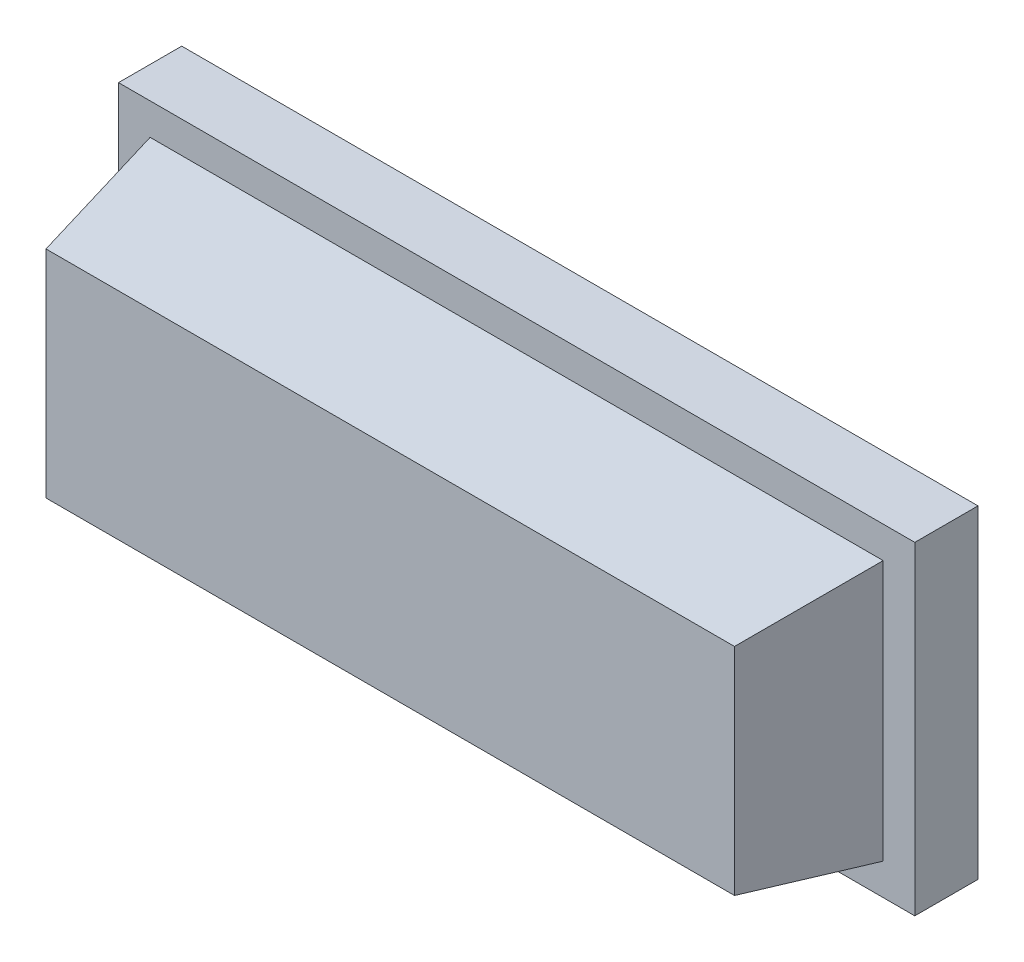
SolidWorks part; units mm, degrees
ref_plane "Front Plane" through (0, 0, 0) normal (0, 0, 1) x (1, 0, 0)
ref_plane "Top Plane" through (0, 0, 0) normal (0, 1, 0) x (1, 0, 0)
ref_plane "Right Plane" through (0, 0, 0) normal (1, 0, 0) x (0, 0, -1)
sketch "Sketch1" plane through (0, 0, 0) normal (0, 0, 1) x (1, 0, 0)
  line L0 (-1.6, -0.65) -> (1.6, 0.65) construction
  line L1 (-1.6, 0.65) -> (1.6, 0.65)
  line L2 (-1.6, 0.65) -> (-1.6, -0.65)
  line L3 (-1.6, -0.65) -> (1.6, -0.65)
  line L4 (1.6, 0.65) -> (1.6, -0.65)
  point P4 (0, 0)
  dimension "D1" = 3.2
  dimension "D2" = 1.3
extrude "Boss-Extrude1" add sketch "Sketch1" along normal blind 0.254
sketch "Sketch2" plane through (0, 0, 0.254) normal (0, 0, 1) x (1, 0, 0)
  line L0 (-1.473, -0.523) -> (1.473, 0.523) construction
  line L1 (-1.473, 0.523) -> (1.473, 0.523)
  line L2 (-1.473, 0.523) -> (-1.473, -0.523)
  line L3 (-1.473, -0.523) -> (1.473, -0.523)
  line L4 (1.473, 0.523) -> (1.473, -0.523)
  line L5 (1.6, 0.65) -> (-1.6, 0.65) construction
  line L6 (-1.6, 0.65) -> (-1.6, -0.65) construction
  point P4 (0, 0)
  dimension "D1" = 0.127
  dimension "D2" = 0.127
extrude "Boss-Extrude2" add sketch "Sketch2" along normal blind 0.508 draft 10
